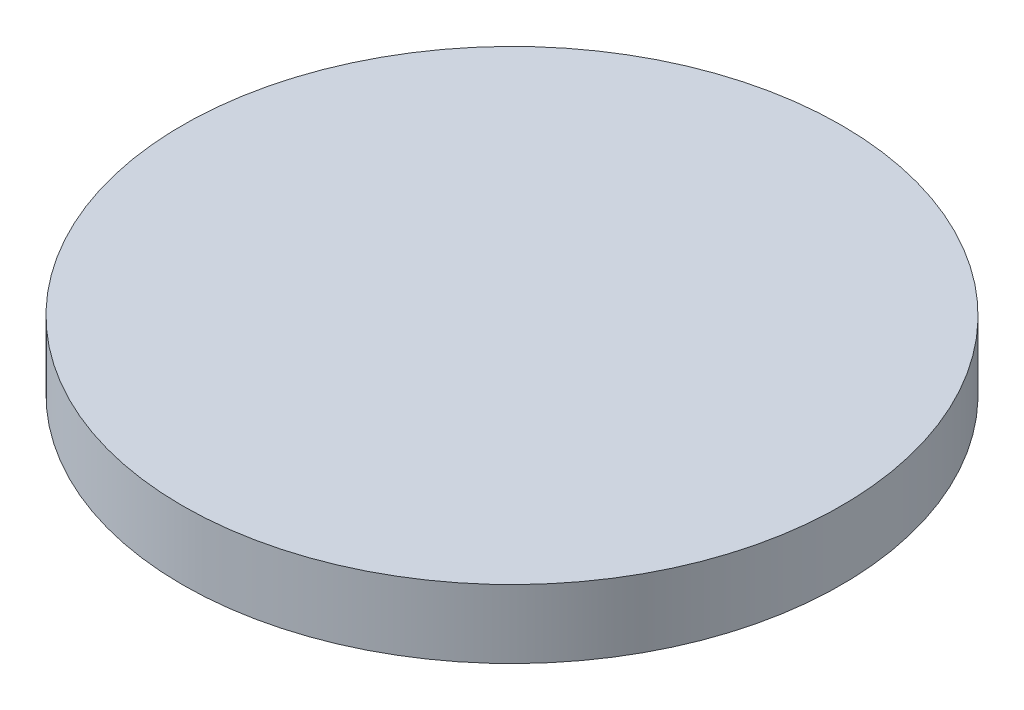
SolidWorks part; units mm, degrees
ref_plane "Front Plane" through (0, 0, 0) normal (0, 0, 1) x (1, 0, 0)
ref_plane "Top Plane" through (0, 0, 0) normal (0, 1, 0) x (1, 0, 0)
ref_plane "Right Plane" through (0, 0, 0) normal (1, 0, 0) x (0, 0, -1)
sketch "Sketch1" plane through (0, 0, 0) normal (0, 1, 0) x (1, 0, 0)
  circle A0 centre (0, 0) radius 14.45
  dimension "D1" = 28.9
extrude "Boss-Extrude1" add sketch "Sketch1" along normal blind 3
